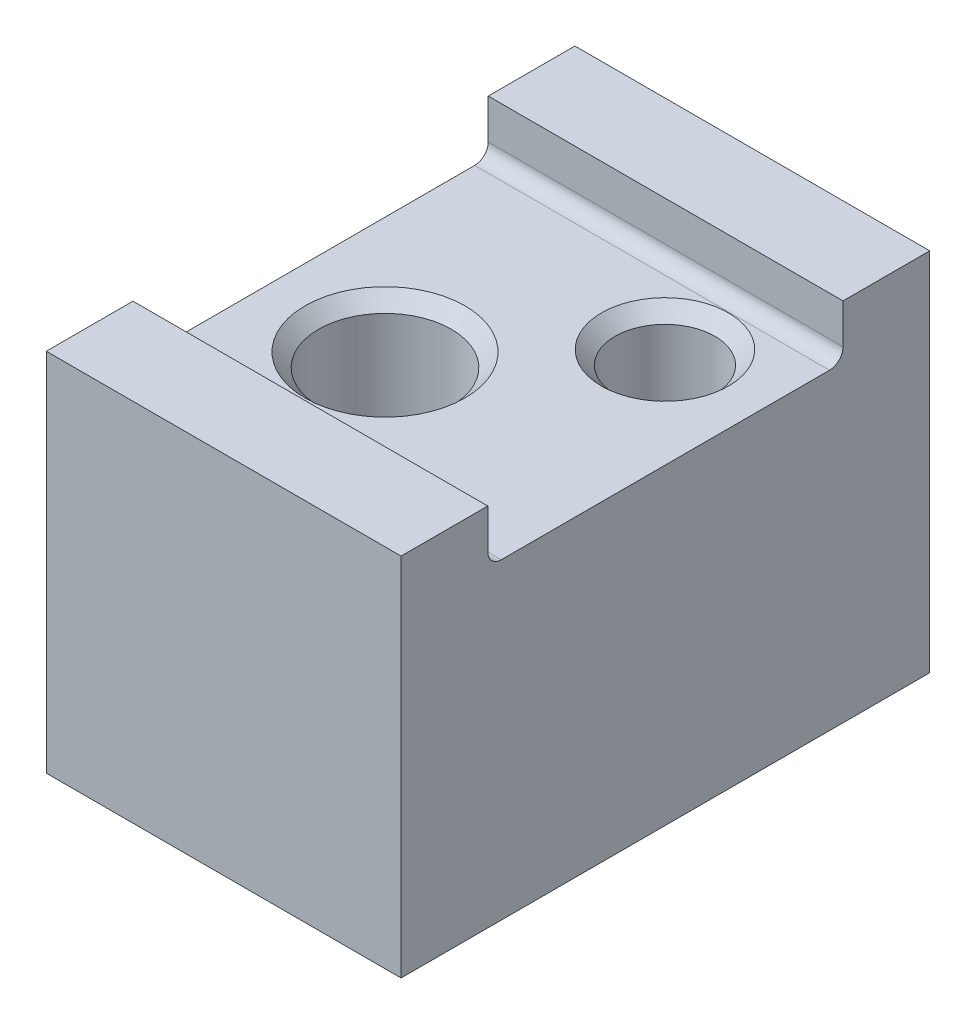
SolidWorks part; units mm, degrees
ref_plane "Front Plane" through (0, 0, 0) normal (0, 0, 1) x (1, 0, 0)
ref_plane "Top Plane" through (0, 0, 0) normal (0, 1, 0) x (1, 0, 0)
ref_plane "Right Plane" through (0, 0, 0) normal (1, 0, 0) x (0, 0, -1)
sketch "Sketch1" plane through (0, 0, 0) normal (0, 1, 0) x (1, 0, 0)
  line L1 (-7.1501, -7.9375) -> (7.1501, -7.9375)
  line L2 (-7.1501, -7.9375) -> (-7.1501, 7.9375)
  line L3 (-7.1501, 7.9375) -> (7.1501, 7.9375)
  line L4 (7.1501, -7.9375) -> (7.1501, 7.9375)
  line L5 (-7.1501, -7.9375) -> (7.1501, 7.9375) construction
  line L6 (-7.1501, 7.9375) -> (7.1501, -7.9375) construction
  dimension "D1" = 15.875
  dimension "D2" = 14.3002
extrude "Boss-Extrude1" add sketch "Sketch1" along normal blind 10.9728
sketch "Sketch5" plane through (7.1501, 0, 0) normal (1, 0, 0) x (0, 0, -1)
  line L0 (-7.9375, 10.9728) -> (7.9375, 10.9728) construction
  line L1 (-5.334, 10.9728) -> (5.334, 10.9728)
  line L2 (-5.334, 10.9728) -> (-5.334, 9.779)
  line L3 (-4.9276, 9.3726) -> (4.9276, 9.3726)
  line L4 (5.334, 10.9728) -> (5.334, 9.779)
  arc A0 (5.334, 9.779) -> (4.9276, 9.3726) centre (4.9276, 9.779) cw
  arc A1 (-4.9276, 9.3726) -> (-5.334, 9.779) centre (-4.9276, 9.779) cw
  point P6 (0, 9.3726)
  point P13 (-5.334, 9.3726)
  dimension "D3" = 0.4064
  dimension "D1" = 1.6002
  dimension "D2" = 10.668
extrude "Cut-Extrude1" cut sketch "Sketch5" against normal through all both and the other way through all
sketch "Sketch3" plane through (0, 0, 0) normal (1, 0, 0) x (0, 0, -1)
  line L0 (-3.6703, 9.3726) -> (-3.2639, 8.9662)
  line L1 (-3.2639, 2.2098) -> (-2.7686, 1.7145)
  line L2 (-3.2639, 8.9662) -> (-3.2639, 2.2098)
  line L3 (-7.9375, 0) -> (7.9375, 0) construction
  line L4 (-2.7686, 0) -> (-1.27, 0)
  line L5 (-1.27, 0) -> (-1.27, 9.3726)
  line L6 (-1.27, 9.3726) -> (-3.6703, 9.3726)
  line L7 (-4.9276, 9.3726) -> (4.9276, 9.3726) construction
  line L8 (-2.7686, 1.7145) -> (-2.7686, 0)
  point P5 (-2.7686, -0.7878)
  dimension "D1" = 45
  dimension "D2" = 1.9939
  dimension "D3" = 0.4064
  dimension "D4" = 1.27
  dimension "D5" = 1.4986
  dimension "D6" = 7.1628
revolve "Cut-Revolve1" cut sketch "Sketch3" angle 360 about L5
ref_plane "Plane1" through (4.1402, 0, 0) normal (1, 0, 0) x (0, 0, -1)
sketch "Sketch4" plane through (4.1402, 0, 0) normal (1, 0, 0) x (0, 0, -1)
  line L0 (2.9972, 10.9728) -> (2.9972, 0)
  line L2 (-7.9375, 0) -> (7.9375, 0) construction
  line L3 (2.9972, 0) -> (4.4972, 0)
  line L4 (4.4972, 0) -> (4.4972, 8.9662)
  line L5 (4.4972, 8.9662) -> (4.9036, 9.3726)
  line L7 (0.7239, 8.9662) -> (-3.2639, 8.9662) construction
  line L8 (0.7239, 8.9662) -> (-3.2639, 8.9662) construction
  line L9 (-1.27, 8.9662) -> (-1.27, 5.4864) construction
  line L10 (-1.27, 5.4864) -> (2.9972, 5.4864) construction
  line L13 (4.9036, 9.3726) -> (4.9036, 10.9728)
  line L14 (4.9036, 10.9728) -> (2.9972, 10.9728)
  line L15 (-4.9276, 9.3726) -> (4.9276, 9.3726) construction
  line L16 (5.334, 10.9728) -> (7.9375, 10.9728) construction
  dimension "D1" = 135
  dimension "D2" = 0.4064
  dimension "D3" = 1.5
  dimension "D4" = 4.2672
revolve "Cut-Revolve2" cut sketch "Sketch4" angle 360 about L0
sketch "Sketch6" plane through (0, 10.9728, 0) normal (0, 1, 0) x (1, 0, 0)
  line L0 (-7.1501, -7.9375) -> (7.1501, -7.9375) construction
  line L1 (-7.1501, 7.9375) -> (-3.5038, 7.9375)
  line L2 (-7.1501, 7.9375) -> (-7.1501, -7.9375)
  line L3 (-7.1501, -7.9375) -> (-3.5038, -7.9375)
  line L4 (-3.5038, 7.9375) -> (-3.5038, -7.9375)
  line L5 (0, -1.27) -> (-2.4003, -1.27) construction
  line L6 (-2.4003, -1.27) -> (-3.5038, -1.27) construction
  line L7 (4.1402, 2.9972) -> (6.0466, 2.9972) construction
  line L8 (6.0466, 2.9972) -> (7.1501, 2.9972) construction
  line L9 (7.1501, -4.9276) -> (7.1501, 4.9276) construction
  circle A0 centre (0, -1.27) radius 2.4003 construction
  circle A1 centre (4.1402, 2.9972) radius 1.9064 construction
extrude "Cut-Extrude2" cut sketch "Sketch6" against normal through all both and the other way through all
